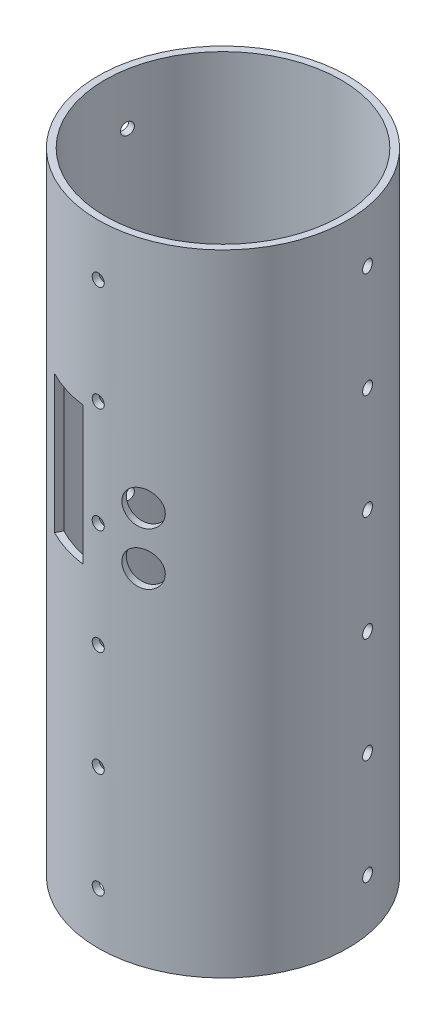
SolidWorks part; units mm, degrees
ref_plane "Front Plane" through (0, 0, 0) normal (0, 0, 1) x (1, 0, 0)
ref_plane "Top Plane" through (0, 0, 0) normal (0, 1, 0) x (1, 0, 0)
ref_plane "Right Plane" through (0, 0, 0) normal (1, 0, 0) x (0, 0, -1)
ref_plane "BULK LENGTH LIMIT" through (0, 183, 0) normal (0, 1, 0) x (1, 0, 0)
ref_axis "Axis1" through (0, 146.5, 0) along (0, -1, 0)
sketch "Sketch1" plane through (0, 0, 0) normal (0, 1, 0) x (1, 0, 0)
  circle A0 centre (0, 0) radius 34.25
  circle A1 centre (0, 0) radius 36.25
  dimension "D1" = 68.5
  dimension "D2" = 2
extrude "BULK" add sketch "Sketch1" along normal up to surface (183 mm away) up to plane "BULK LENGTH LIMIT"
sketch "Sketch2" plane through (0, 0, 0) normal (0, 0, 1) x (1, 0, 0)
  line L0 (39.875, 183) -> (-39.875, 183) construction
  circle A0 centre (0, 15) radius 1.75
  circle A1 centre (0, 45.6) radius 1.75
  circle A2 centre (0, 76.2) radius 1.75
  circle A3 centre (0, 106.8) radius 1.75
  circle A4 centre (0, 137.4) radius 1.75
  circle A5 centre (0, 168) radius 1.75
  dimension "D2" = 3.5
  dimension "D1" = 15
  dimension "D4" = 15
  dimension "D3" = 6
extrude "FRONT HOLE CUTOUT" cut sketch "Sketch2" along normal through all
pattern_circular "CirPattern1" count 2 every 100 about axis through (0, 146.5, 0) along (0, -1, 0) of "FRONT HOLE CUTOUT"
mirror "Mirror1" about plane through (0, 0, 0) normal (1, 0, 0) of "CirPattern1"
ref_plane "Plane2" through (0, 0, 0) normal (0.9914, 0, 0.1305) x (0, -1, 0)
sketch "Sketch3" plane through (0, 0, 0) normal (0.9914, 0, 0.1305) x (0, -1, 0)
  line L0 (-146.5, 0) -> (-36.5, 0) construction
  line L1 (-94.02, -50) -> (-134.02, -50)
  line L2 (-94.02, -50) -> (-94.02, 0)
  line L3 (-94.02, 0) -> (-134.02, 0)
  line L4 (-134.02, -50) -> (-134.02, 0)
  ellipse E0 centre (-106.8, 0) end of major axis (-108.55, 0) minor radius 0.2284 construction
  dimension "D1" = 40
  dimension "D2" = 50
  dimension "D3" = 12.78
revolve "Cut-Revolve1" cut sketch "Sketch3" angle 20 about axis through (0, 146.5, 0) along (0, -1, 0)
ref_plane "Plane3" through (0, 0, 0) normal (0.9511, 0, -0.309) x (0, -1, 0)
ref_plane "Plane4" through (11.2019, 0, 34.4758) normal (0.309, 0, 0.9511) x (0.9511, 0, -0.309)
sketch "Sketch4" plane through (11.2019, 0, 34.4758) normal (0.309, 0, 0.9511) x (0.9511, 0, -0.309)
  line L0 (0, -60.5) -> (0, 60.5) construction
  circle A0 centre (0, 115.3) radius 5
  circle A1 centre (0, 100.1) radius 5
  dimension "D2" = 10
  dimension "D1" = 15.2
  dimension "D3" = 52.7
extrude "Cut-Extrude2" cut sketch "Sketch4" against normal up to next
